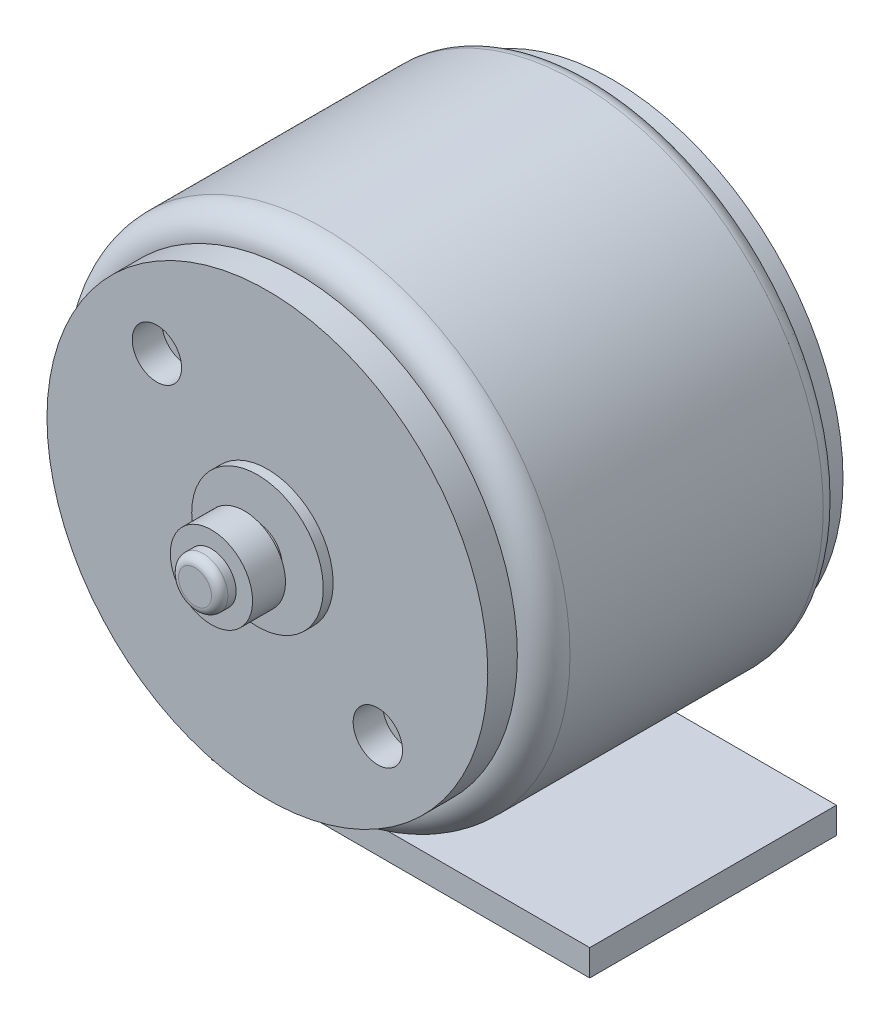
SolidWorks part; units mm, degrees
ref_plane "Front" through (0, 0, 0) normal (0, 0, 1) x (1, 0, 0)
ref_plane "Top" through (0, 0, 0) normal (0, 1, 0) x (1, 0, 0)
ref_plane "Right" through (0, 0, 0) normal (1, 0, 0) x (0, 0, -1)
sketch "Эскиз1" plane through (0, 0, 0) normal (0, 1, 0) x (1, 0, 0)
  line L0 (0, 0) -> (0, -19.3752) construction
  line L1 (0, 0) -> (-0.5, 0)
  line L3 (-0.75, -0.5) -> (-3, -0.5)
  line L4 (-3, -0.5) -> (-3, -1.5)
  line L5 (-3, -1.5) -> (-7, -1.5)
  line L6 (-7, -1.5) -> (-7, -2.1)
  line L8 (-7.5, -2.6) -> (-7.5, -10.3)
  line L10 (-6.7, -11.1) -> (-6.7, -12)
  line L11 (-6.7, -12) -> (-2, -12)
  line L12 (0, -12) -> (0, 0)
  line L14 (-7, -2.1) -> (-7, -2.6) construction
  line L15 (-6.7, -11.1) -> (-6.7, -10.3) construction
  line L16 (-6.7, -11.1) -> (-7.5, -11.1) construction
  line L26 (0, -14.2) -> (-0.5, -14.2)
  line L27 (-0.75, -0.5) -> (-0.75, -0.25)
  line L28 (0, -12) -> (-2, -12) construction
  line L29 (-2, -12) -> (-2, -12.3)
  line L30 (0, -14.2) -> (0, -12)
  line L31 (-2, -12.3) -> (-0.75, -12.3)
  line L32 (-0.75, -12.3) -> (-0.75, -13.95) construction
  line L33 (-0.75, -12.3) -> (-0.75, -12.7)
  line L34 (-0.75, -12.7) -> (-1.25, -12.7)
  line L35 (-1.25, -12.7) -> (-1.25, -13.7)
  line L36 (-1.25, -13.7) -> (-0.75, -13.7)
  line L37 (-0.75, -13.7) -> (-0.75, -13.95)
  arc A0 (-7, -2.1) -> (-7.5, -2.6) centre (-7, -2.6) ccw
  arc A1 (-7.5, -10.3) -> (-6.7, -11.1) centre (-6.7, -10.3) ccw
  arc A2 (-0.75, -13.95) -> (-0.5, -14.2) centre (-0.5, -13.95) ccw
  arc A3 (-0.5, 0) -> (-0.75, -0.25) centre (-0.5, -0.25) ccw
  point P29 (-0.25, -14.2)
  point P37 (0, 0)
  point P38 (-0.75, -12.7137)
  dimension "D1" = 6
  dimension "D7" = 0.9
  dimension "D10" = 10.5
  dimension "D16" = 4
  dimension "D4" = 0.5
  dimension "D5" = 0.25
  dimension "D2" = 15
  dimension "D3" = 1
  dimension "D6" = 0.6
  dimension "D8" = 14
  dimension "D9" = 13.4
  dimension "D17" = 1.5
  dimension "D18" = 0.3
  dimension "D19" = 2.5
  dimension "2,2" = 2.2
  dimension "D20" = 0.75
  dimension "D21" = 1
  dimension "D22" = 0.4
revolve "Motor" add sketch "Эскиз1" angle 360 about L0
ref_plane "Плоскость1" through (0, -7.5, 0) normal (0, -1, 0) x (-1, 0, 0)
sketch "Эскиз4" plane through (0, -7.5, 0) normal (0, -1, 0) x (-1, 0, 0)
  line L0 (0, -2.6) -> (0, -10.3) construction
  line L1 (3.5, -10.2) -> (-8, -10.2)
  line L2 (3.5, -10.2) -> (3.5, -2.7)
  line L3 (3.5, -2.7) -> (-8, -2.7)
  line L4 (-8, -10.2) -> (-8, -2.7)
  line L5 (3.5, -6.45) -> (-8, -6.45) construction
  line L7 (7.5, -10.3) -> (-7.5, -10.3) construction
  line L8 (7.5, -2.6) -> (-7.5, -2.6) construction
  point P5 (0, -6.45)
  dimension "D1" = 7.5
  dimension "D2" = 11.5
  dimension "D3" = 3.5
extrude "Плата" add sketch "Эскиз4" along normal blind 0.8 separate body
sketch "Пайка контактов" plane through (0, -8.3, 0) normal (0, -1, 0) x (1, 0, 0)
  line L0 (-0.75, 7.2) -> (2.25, 7.2) construction
  line L1 (0.75, 5.7) -> (-2.25, 5.7) construction
  line L2 (-0.75, 5.7) -> (-0.75, 7.2) construction
  line L3 (-0.75, 6.45) -> (-3.5, 6.45) construction
  line L4 (-3.5, 10.2) -> (-3.5, 2.7) construction
  line L5 (-0.75, 7.2) -> (0.75, 5.7) construction
  line L6 (0, 6.45) -> (0, 0) construction
  line L8 (7, 5.5333) -> (7, 3.7) construction
  line L9 (7, 7.3667) -> (7, 5.5333) construction
  line L10 (7, 7.3667) -> (7, 9.2) construction
  line L11 (7, 6.45) -> (8, 6.45) construction
  line L12 (8, 2.7) -> (8, 10.2) construction
  circle A0 centre (-2.25, 5.7) radius 0.75
  circle A1 centre (-0.75, 7.2) radius 0.75
  circle A2 centre (0.75, 5.7) radius 0.75
  circle A3 centre (2.25, 7.2) radius 0.75
  circle A4 centre (7, 3.7) radius 0.75
  circle A5 centre (7, 5.5333) radius 0.75
  circle A6 centre (7, 7.3667) radius 0.75
  circle A7 centre (7, 9.2) radius 0.75
  point P14 (-3.5, 6.45)
  point P29 (8, 6.45)
  dimension "D1" = 1.5
  dimension "D4" = 1.5
  dimension "D2" = 3
  dimension "D3" = 1.5
  dimension "D5" = 5.5
  dimension "D6" = 1
extrude "Бобышка-Вытянуть3" add sketch "Пайка контактов" along normal blind 0.7 draft 35
sketch "Эскиз6" plane through (0, -8.3, 0) normal (0, -1, 0) x (1, 0, 0)
  line L0 (5.7717, 10.2) -> (5.7717, 2.7) construction
  line L1 (8, 10.2) -> (-3.5, 10.2) construction
  line L2 (-3.5, 2.7) -> (8, 2.7) construction
  line L3 (-3.5, 8.1932) -> (8, 8.1932) construction
  line L4 (-3.5, 10.2) -> (-3.5, 2.7) construction
  line L5 (8, 2.7) -> (8, 10.2) construction
  text T0 "B1 B2 A1 A2" font "Century Gothic" height 0.85
  text T1 " B1 A2 B2 A1" font "Century Gothic" height 0.8
extrude "Бобышка-Вытянуть4" add sketch "Эскиз6" along normal blind 0.01
sketch "Эскиз7" plane through (0, 0, 12) normal (0, 0, 1) x (1, 0, 0)
  line L0 (-3.3588, 3.3588) -> (3.3588, -3.3588) construction
  line L1 (0, 0) -> (0, -5.0865) construction
  circle A0 centre (3.3588, -3.3588) radius 0.75
  circle A1 centre (-3.3588, 3.3588) radius 0.75
  point P4 (0, 0)
  dimension "D1" = 45
  dimension "D2" = 1.5
  dimension "D3" = 9.5
extrude "Вырез-Вытянуть1" cut sketch "Эскиз7" against normal blind 0.9
